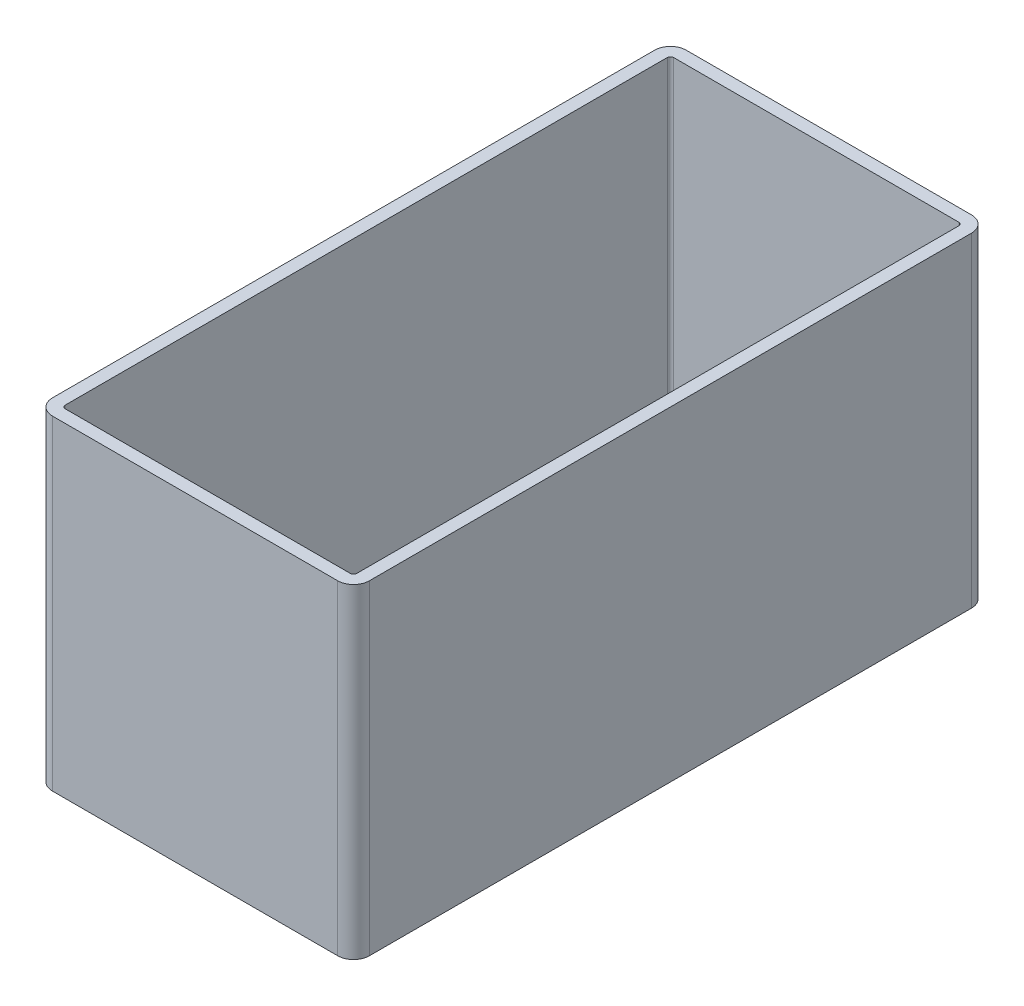
SolidWorks part; units mm, degrees
material "PC High Viscosity"
ref_plane "Front Plane" through (0, 0, 0) normal (0, 0, 1) x (1, 0, 0)
ref_plane "Top Plane" through (0, 0, 0) normal (0, 1, 0) x (1, 0, 0)
ref_plane "Right Plane" through (0, 0, 0) normal (1, 0, 0) x (0, 0, -1)
sketch "BaseS" plane through (0, 0, 0) normal (0, 1, 0) x (1, 0, 0)
  line L1 (-10, 20) -> (10, 20)
  line L2 (-10, 20) -> (-10, -20)
  line L3 (-10, -20) -> (10, -20)
  line L4 (10, 20) -> (10, -20)
  line L5 (-10, 20) -> (10, -20) construction
  line L6 (-10, -20) -> (10, 20) construction
  point P0 (0, 0)
  dimension "D1" = 20
  dimension "D2" = 40
extrude "BASE" add sketch "BaseS" along normal mid plane 20.5
fillet "BASE F" radius 1 4 edges at (-10, 0, -20) (10, 0, -20) (10, 0, 20) (-10, 0, 20)
sketch "PocketS" plane through (0, 10.25, 0) normal (0, 1, 0) x (1, 0, 0)
  line L0 (9, 19.2) -> (-9, 19.2)
  line L1 (-9.2, 19) -> (-9.2, -19)
  line L2 (-9, -19.2) -> (9, -19.2)
  line L3 (9.2, -19) -> (9.2, 19)
  line L4 (9, 20) -> (-9, 20)
  line L5 (-10, 19) -> (-10, -19)
  line L6 (-9, -20) -> (9, -20)
  line L7 (10, -19) -> (10, 19)
  line L8 (9, 20) -> (-9, 20) construction
  line L9 (-10, 19) -> (-10, -19) construction
  line L10 (-9, -20) -> (9, -20) construction
  line L11 (10, -19) -> (10, 19) construction
  arc A0 (-9, 19.2) -> (-9.2, 19) centre (-9, 19) ccw
  arc A1 (-9.2, -19) -> (-9, -19.2) centre (-9, -19) ccw
  arc A2 (9, -19.2) -> (9.2, -19) centre (9, -19) ccw
  arc A3 (9.2, 19) -> (9, 19.2) centre (9, 19) ccw
  arc A4 (-9, 20) -> (-10, 19) centre (-9, 19) ccw
  arc A5 (-10, -19) -> (-9, -20) centre (-9, -19) ccw
  arc A6 (9, -20) -> (10, -19) centre (9, -19) ccw
  arc A7 (10, 19) -> (9, 20) centre (9, 19) ccw
  arc A8 (-9, 20) -> (-10, 19) centre (-9, 19) ccw construction
  arc A9 (-10, -19) -> (-9, -20) centre (-9, -19) ccw construction
  arc A10 (9, -20) -> (10, -19) centre (9, -19) ccw construction
  arc A11 (10, 19) -> (9, 20) centre (9, 19) ccw construction
  dimension "D1" = 0
  dimension "D2" = 0.8
extrude "Cut-Extrude3" cut sketch "PocketS" against normal through all
